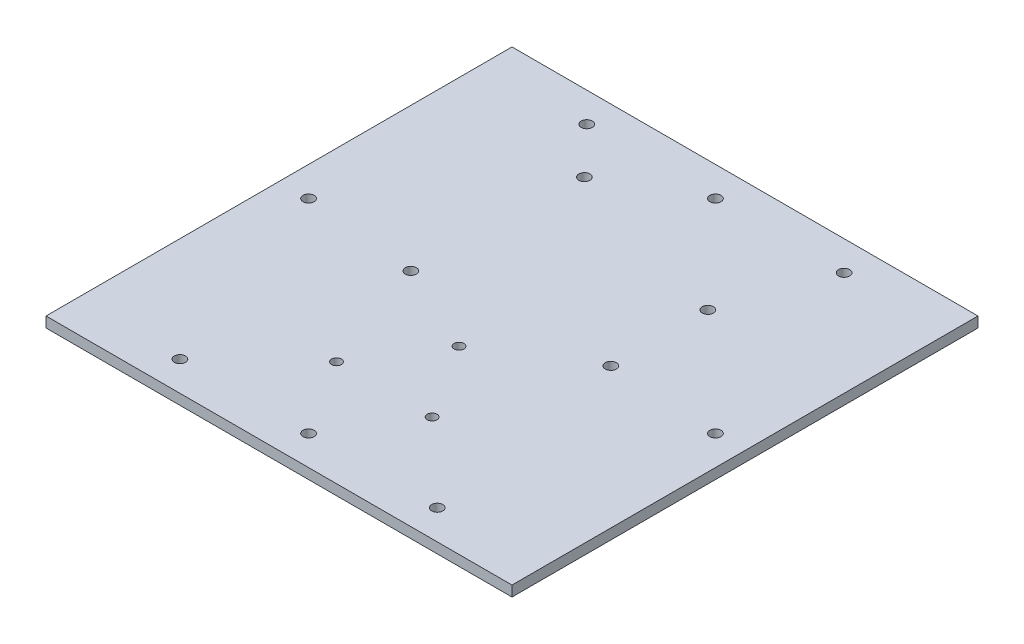
SolidWorks part; units mm, degrees
ref_plane "Front Plane" through (0, 0, 0) normal (0, 0, 1) x (1, 0, 0)
ref_plane "Top Plane" through (0, 0, 0) normal (0, 1, 0) x (1, 0, 0)
ref_plane "Right Plane" through (0, 0, 0) normal (1, 0, 0) x (0, 0, -1)
sketch "Sketch2" plane through (0, 0, 0) normal (0, 1, 0) x (1, 0, 0)
  line L0 (-67, 67) -> (67, -67) construction
  line L1 (-67, 67) -> (67, 67)
  line L2 (-67, 67) -> (-67, -67)
  line L3 (-67, -67) -> (67, -67)
  line L4 (67, 67) -> (67, -67)
  line L5 (67, 67) -> (-67, -67) construction
  line L6 (-0.0804, -25.9435) -> (-0.0804, -44.0256) construction
  line L7 (-50, 50) -> (50, -50) construction
  line L8 (50, 50) -> (-50, 50)
  line L9 (50, 50) -> (50, -50)
  line L10 (50, -50) -> (-50, -50)
  line L11 (-50, 50) -> (-50, -50)
  line L12 (50, 50) -> (-50, -50) construction
  line L13 (-25.7654, -3.3155) -> (-25.7654, 44.9845) construction
  line L14 (26.6346, 1.7845) -> (14.9379, 1.7845)
  line L15 (-25.7654, -3.3155) -> (14.9379, -3.3155)
  line L16 (14.9379, -3.3155) -> (14.9379, 1.7845)
  line L17 (0, 67) -> (0, -67) construction
  line L18 (-67, 0) -> (67, 0) construction
  line L19 (0, 67) -> (0, 50) construction
  line L20 (-50, 0) -> (-67, 0) construction
  line L21 (0, -50) -> (0, -67) construction
  line L22 (50, 0) -> (67, 0) construction
  line L23 (-37, 67) -> (-37, -67) construction
  line L24 (37, 67) -> (37, -67) construction
  line L25 (-37, 50) -> (-37, 67) construction
  line L26 (37, 50) -> (37, 67) construction
  line L27 (-37, -50) -> (-37, -67) construction
  line L28 (37, -50) -> (37, -67) construction
  circle A0 centre (-0.0804, -15.1435) radius 1.4
  circle A1 centre (-13.8304, -36.6435) radius 1.4
  circle A2 centre (13.6696, -36.6435) radius 1.4
  circle A3 centre (-24.1654, 44.9845) radius 1.6
  circle A4 centre (-25.7654, -3.3155) radius 1.6
  circle A5 centre (26.6346, 29.6845) radius 1.6
  circle A6 centre (26.6346, 1.7845) radius 1.6
  circle A10 centre (0, 58.5) radius 1.6
  circle A11 centre (-58.5, 0) radius 1.6
  circle A12 centre (0, -58.5) radius 1.6
  circle A13 centre (58.5, 0) radius 1.6
  circle A14 centre (-37, 58.5) radius 1.6
  circle A15 centre (37, 58.5) radius 1.6
  circle A16 centre (-37, -58.5) radius 1.6
  circle A17 centre (37, -58.5) radius 1.6
  point P12 (0, 0)
  point P18 (0, 0)
  point P40 (0, 58.5)
  point P44 (-58.5, 0)
  point P49 (0, -58.5)
  point P54 (58.5, 0)
  point P63 (-37, 58.5)
  point P68 (37, 58.5)
  point P73 (-37, -58.5)
  point P77 (0, 0)
  point P78 (37, -58.5)
  dimension "D3" = 30
  dimension "2.8" = 2.8
  dimension "D9" = 3.2
  dimension "D1" = 134
  dimension "D2" = 100
  dimension "D4" = 50.8
  dimension "D5" = 27.9
  dimension "D6" = 5.1
  dimension "D7" = 48.3
  dimension "D8" = 40.7033
  dimension "D10" = 30
extrude "Boss-Extrude2" add sketch "Sketch2" along normal blind 3
